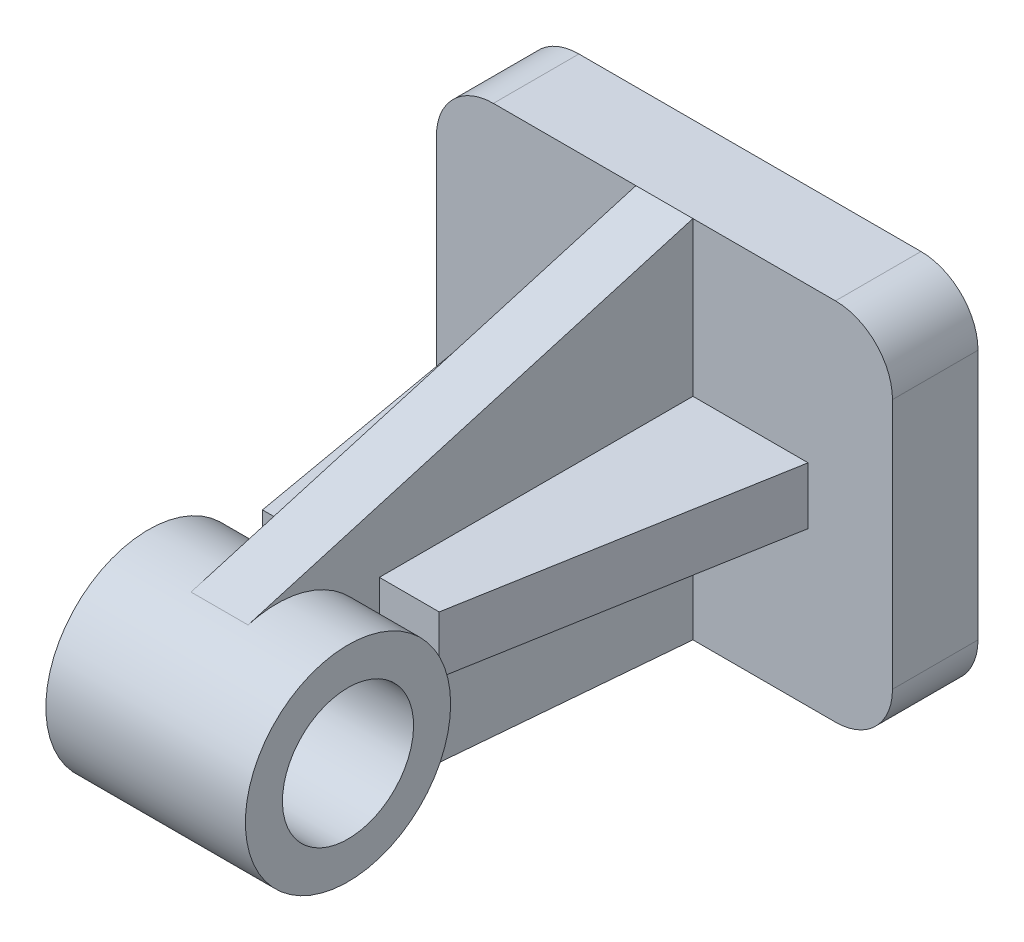
SolidWorks part; units mm, degrees
ref_plane "Front Plane" through (0, 0, 0) normal (1, 0, 0) x (0, 1, 0)
ref_plane "Top Plane" through (0, 0, 0) normal (0, 0, 1) x (0, 1, 0)
ref_plane "Right Plane" through (0, 0, 0) normal (0, 1, 0) x (-1, 0, 0)
sketch "Sketch1" plane through (0, 0, 0) normal (0, 0, 1) x (0, 1, 0)
  line L1 (-32, 40) -> (32, 40)
  line L2 (-32, 40) -> (-32, -40)
  line L3 (-32, -40) -> (32, -40)
  line L4 (32, 40) -> (32, -40)
  line L5 (0, -40) -> (0, 40) construction
  line L6 (-32, 0) -> (32, 0) construction
  point P0 (0, 0)
  dimension "D1" = 80
  dimension "D2" = 64
extrude "Boss-Extrude1" add sketch "Sketch1" along normal blind 15
fillet "Fillet2" radius 10 4 edges at (40, 32, 7.5) (-40, -32, 7.5) (-40, 32, 7.5) (40, -32, 7.5)
sketch "Sketch2" plane through (0, 0, 0) normal (1, 0, 0) x (0, 1, 0)
  line L0 (-32, 0) -> (-32, 15) construction
  line L1 (-22, 0) -> (22, 0) construction
  circle A0 centre (-8, 88) radius 18
  point P6 (48.7158, 72.4687)
  dimension "D1" = 36
  dimension "D2" = 24
  dimension "D3" = 88
extrude "Extrude-Thin1" add sketch "Sketch2" along normal mid plane 35 separate body thin thin type one direction reverse wall 6.5
sketch "Sketch3" plane through (0, 0, 0) normal (1, 0, 0) x (0, 1, 0)
  line L0 (-32, 15) -> (-25.9407, 89.46)
  line L1 (9.2825, 93.0315) -> (32, 15)
  line L2 (32, 15) -> (32, 0) construction
  line L3 (32, 15) -> (22, 15) construction
  line L4 (32, 15) -> (-32, 15)
  circle A0 centre (-8, 88) radius 18 construction
  circle A2 centre (-8, 88) radius 18
  circle A3 centre (-8, 88) radius 18
  dimension "D1" = 0
extrude "Boss-Extrude2" add sketch "Sketch3" along normal mid plane 10 contours A3 L0 L4 L1
sketch "Sketch4" plane through (0, 0, 0) normal (0, 1, 0) x (-1, 0, 0)
  line L0 (-15.5, 70) -> (-25.198, 15)
  line L1 (-17.5, 70) -> (-5, 70) construction
  line L2 (-30, 15) -> (-40, 15) construction
  line L3 (-15.5, 70) -> (15.5, 70)
  line L4 (0, 70) -> (0, 15) construction
  line L5 (-5, 15) -> (5, 15) construction
  line L6 (25.198, 15) -> (-25.198, 15)
  line L7 (0, 35.2) -> (0, -35.2) construction
  line L8 (15.5, 70) -> (25.198, 15)
  dimension "D1" = 2
  dimension "D2" = 80
extrude "Boss-Extrude3" add sketch "Sketch4" along normal mid plane 10
